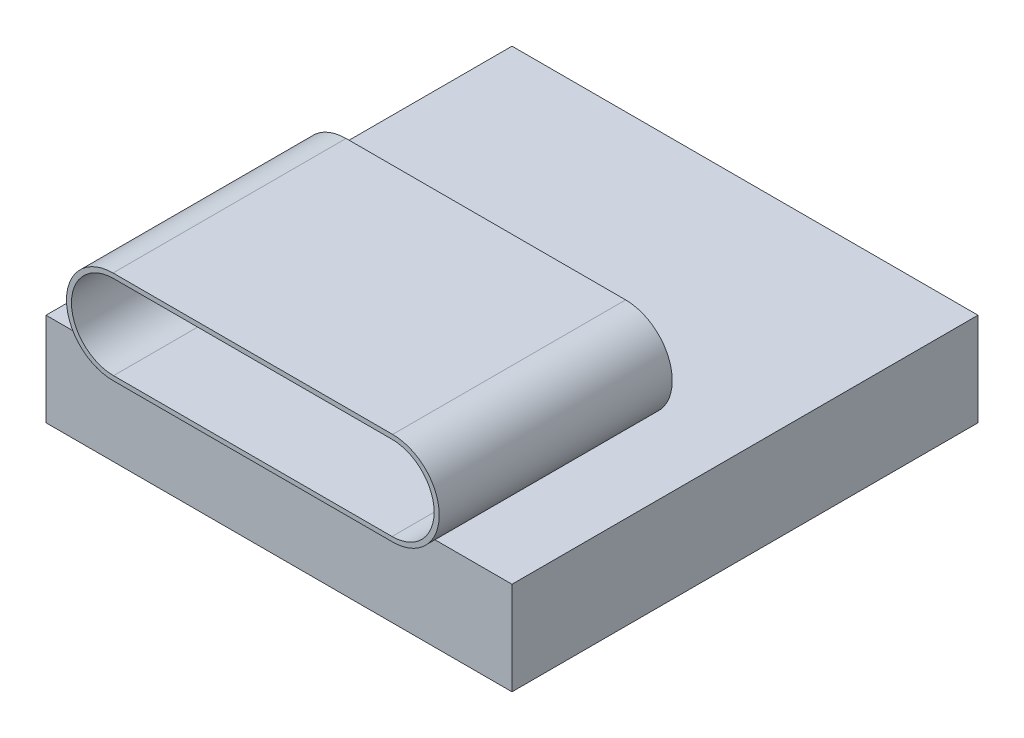
SolidWorks part; units mm, degrees
ref_plane "前视基准面" through (0, 0, 0) normal (0, 0, 1) x (1, 0, 0)
ref_plane "上视基准面" through (0, 0, 0) normal (0, 1, 0) x (1, 0, 0)
ref_plane "右视基准面" through (0, 0, 0) normal (1, 0, 0) x (0, 0, -1)
sketch "草图1" plane through (0, 0, 0) normal (0, 1, 0) x (1, 0, 0)
  line L1 (-5, 6.5) -> (5, 6.5)
  line L2 (-5, 6.5) -> (-5, -6.5)
  line L3 (-5, -6.5) -> (5, -6.5)
  line L4 (5, 6.5) -> (5, -6.5)
  line L5 (-5, 6.5) -> (5, -6.5) construction
  line L6 (-5, -6.5) -> (5, 6.5) construction
  point P0 (0, 0)
extrude "凸台-拉伸1" add sketch "草图1" along normal blind 2
sketch "草图2" plane through (0, 0, 0) normal (0, 0, 1) x (1, 0, 0)
  line L0 (-3.0611, 3.004) -> (2.9389, 3.004) construction
  line L1 (-3.0611, 4.004) -> (2.9389, 4.004)
  line L2 (-3.0611, 2.004) -> (2.9389, 2.004)
  line L3 (-3.0611, 3.004) -> (2.9389, 3.004) construction
  line L4 (-3.0611, 3.9314) -> (2.9389, 3.9314)
  line L5 (-3.0611, 2.0767) -> (2.9389, 2.0767)
  arc A0 (-3.0611, 4.004) -> (-3.0611, 2.004) centre (-3.0611, 3.004) ccw
  arc A1 (2.9389, 2.004) -> (2.9389, 4.004) centre (2.9389, 3.004) ccw
  arc A2 (-3.0611, 3.9314) -> (-3.0611, 2.0767) centre (-3.0611, 3.004) ccw
  arc A3 (2.9389, 2.0767) -> (2.9389, 3.9314) centre (2.9389, 3.004) ccw
  point P2 (-0.0611, 3.004)
  point P9 (-0.0611, 3.004)
extrude "凸台-拉伸3" add sketch "草图2" along normal blind 5 separate body contours A0 L2 A1 L1
ref_plane "基准面4" through (2.9389, 2.004, 0) normal (1, 0, 0) x (0, 0, -1)
sketch "草图5" plane through (0, 0, 5) normal (0, 0, 1) x (1, 0, 0)
  line L0 (-3.0507, 3.0034) -> (2.9262, 3.0034) construction
  line L1 (-3.0507, 3.9061) -> (2.9262, 3.9061)
  line L2 (-3.0507, 2.1006) -> (2.9262, 2.1006)
  arc A0 (-3.0507, 3.9061) -> (-3.0507, 2.1006) centre (-3.0507, 3.0034) ccw
  arc A1 (2.9262, 2.1006) -> (2.9262, 3.9061) centre (2.9262, 3.0034) ccw
  point P2 (-0.0623, 3.0034)
extrude "切除-拉伸1" cut sketch "草图5" against normal through all
sketch "草图10" plane through (0, 0, 6.5) normal (0, 0, 1) x (1, 0, 0)
  line L0 (-5, 0) -> (5, 0) construction
  line L1 (-5, 2) -> (5, 2)
  line L2 (-5, 2) -> (-5, 0)
  line L3 (-5, 0) -> (5, 0)
  line L4 (5, 2) -> (5, 0)
  line L5 (-5, 2) -> (5, 0) construction
  line L6 (-5, 0) -> (5, 2) construction
  point P0 (0, 1)
extrude "切除-拉伸2" cut sketch "草图10" against normal blind 2 contours L1 L4 L3 L2
sketch "草图11" plane through (0, 0, -6.5) normal (0, 0, -1) x (-1, 0, 0)
  line L1 (-5, 2) -> (5, 2)
  line L2 (-5, 2) -> (-5, 0)
  line L3 (-5, 0) -> (5, 0)
  line L4 (5, 2) -> (5, 0)
  line L5 (-5, 2) -> (5, 0) construction
  line L6 (-5, 0) -> (5, 2) construction
  point P0 (0, 1)
extrude "切除-拉伸3" cut sketch "草图11" against normal blind 2
sketch "草图12" plane through (0, 0, -4.5) normal (0, 0, -1) x (-1, 0, 0)
  line L1 (-5, 2) -> (5, 2)
  line L2 (-5, 2) -> (-5, 0)
  line L3 (-5, 0) -> (5, 0)
  line L4 (5, 2) -> (5, 0)
  line L5 (-5, 2) -> (5, 0) construction
  line L6 (-5, 0) -> (5, 2) construction
  point P0 (0, 1)
extrude "凸台-拉伸4" add sketch "草图12" along normal blind 1
